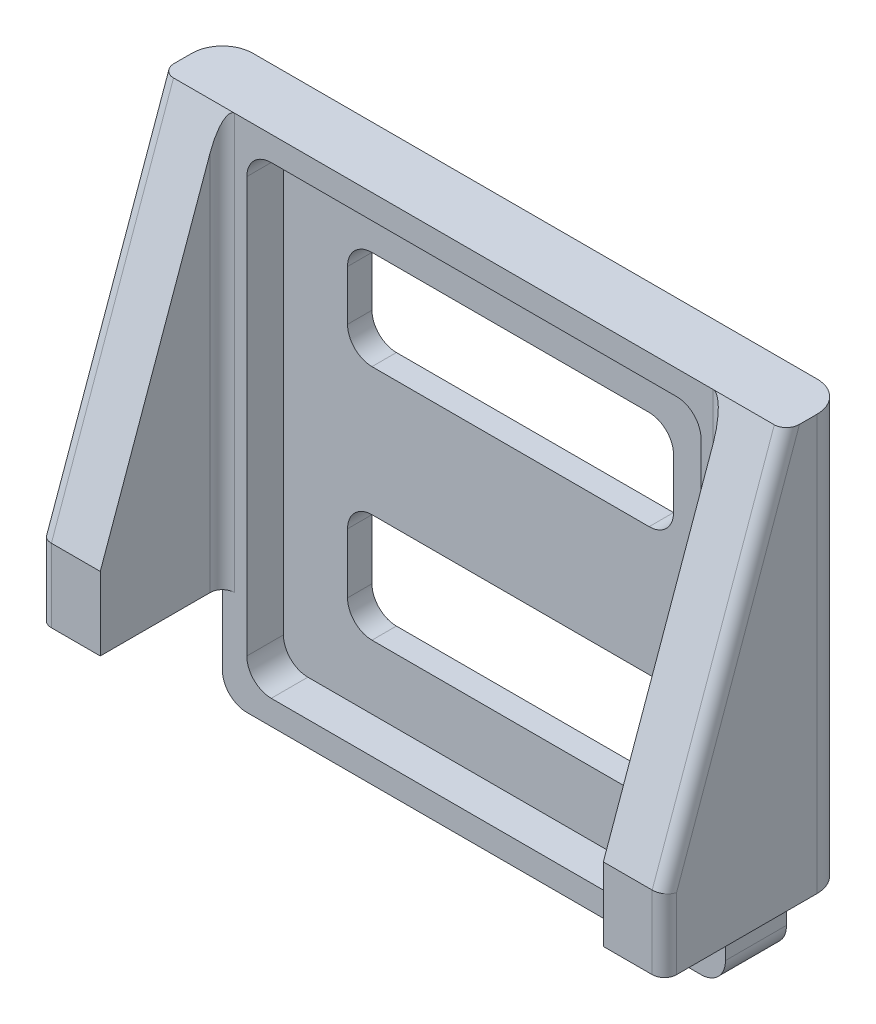
SolidWorks part; units mm, degrees
ref_plane "Front Plane" through (0, 0, 0) normal (0, 0, 1) x (1, 0, 0)
ref_plane "Top Plane" through (0, 0, 0) normal (0, 1, 0) x (1, 0, 0)
ref_plane "Right Plane" through (0, 0, 0) normal (1, 0, 0) x (0, 0, -1)
sketch "Sketch1" plane through (0, 0, 0) normal (0, 0, 1) x (1, 0, 0)
  line L1 (0, 0) -> (41.2, 0)
  line L2 (0, 0) -> (0, -42)
  line L3 (0, -42) -> (41.2, -42)
  line L4 (41.2, 0) -> (41.2, -42)
  dimension "D1" = 41.2
  dimension "D2" = 42
extrude "Boss-Extrude1" add sketch "Sketch1" along normal blind 5 contours L1 L4 L3 L2
sketch "Sketch2" plane through (0, 0, 5) normal (0, 0, 1) x (1, 0, 0)
  line L0 (0, 0) -> (41.2, 0) construction
  line L1 (4, -2) -> (37.2, -2)
  line L2 (2, -4) -> (2, -38)
  line L3 (4, -40) -> (37.2, -40)
  line L4 (39.2, -4) -> (39.2, -38)
  line L5 (0, -42) -> (41.2, -42) construction
  line L6 (0, 0) -> (0, -42) construction
  line L7 (41.2, 0) -> (41.2, -42) construction
  arc A0 (37.2, -2) -> (39.2, -4) centre (37.2, -4) cw
  arc A1 (37.2, -40) -> (39.2, -38) centre (37.2, -38) ccw
  arc A2 (2, -38) -> (4, -40) centre (4, -38) ccw
  arc A3 (4, -2) -> (2, -4) centre (4, -4) ccw
  dimension "D5" = 2
  dimension "D1" = 2
  dimension "D2" = 2
  dimension "D3" = 2
  dimension "D4" = 2
extrude "Cut-Extrude1" cut sketch "Sketch2" against normal blind 3
sketch "Sketch3" plane through (0, 0, 2) normal (0, 0, 1) x (1, 0, 0)
  line L0 (37.2, -2) -> (4, -2) construction
  line L1 (9.25, -7.25) -> (31.95, -7.25)
  line L2 (7.25, -9.25) -> (7.25, -13.35)
  line L3 (9.25, -15.35) -> (31.95, -15.35)
  line L4 (33.95, -9.25) -> (33.95, -13.35)
  line L5 (9.25, -25.85) -> (31.95, -25.85)
  line L6 (7.25, -27.85) -> (7.25, -32.75)
  line L7 (9.25, -34.75) -> (31.95, -34.75)
  line L8 (33.95, -27.85) -> (33.95, -32.75)
  line L9 (4, -40) -> (37.2, -40) construction
  line L10 (2, -4) -> (2, -38) construction
  line L11 (39.2, -38) -> (39.2, -4) construction
  arc A0 (31.95, -34.75) -> (33.95, -32.75) centre (31.95, -32.75) ccw
  arc A1 (7.25, -32.75) -> (9.25, -34.75) centre (9.25, -32.75) ccw
  arc A2 (9.25, -25.85) -> (7.25, -27.85) centre (9.25, -27.85) ccw
  arc A3 (31.95, -25.85) -> (33.95, -27.85) centre (31.95, -27.85) cw
  arc A4 (31.95, -7.25) -> (33.95, -9.25) centre (31.95, -9.25) cw
  arc A5 (31.95, -15.35) -> (33.95, -13.35) centre (31.95, -13.35) ccw
  arc A6 (7.25, -13.35) -> (9.25, -15.35) centre (9.25, -13.35) ccw
  arc A7 (9.25, -7.25) -> (7.25, -9.25) centre (9.25, -9.25) ccw
  dimension "D9" = 2
  dimension "D1" = 5.25
  dimension "D2" = 5.25
  dimension "D3" = 5.25
  dimension "D4" = 5.25
  dimension "D5" = 5.25
  dimension "D6" = 5.25
  dimension "D7" = 10.5
  dimension "D8" = 8.1
extrude "Cut-Extrude2" cut sketch "Sketch3" against normal up to surface (2 mm away) up to face at (20.6, -21, 0)
ref_plane "Plane1" through (0, -34, 0) normal (0, -1, 0) x (-1, 0, 0)
sketch "Sketch6" plane through (41.2, 0, 0) normal (1, 0, 0) x (0, 0, -1)
  line L0 (-5, 0) -> (-5, -42) construction
  line L1 (-5, -28) -> (0, -28)
  line L2 (-5, -28) -> (-5, -34)
  line L3 (-5, -34) -> (0, -34)
  line L4 (0, -28) -> (0, -34)
  line L5 (0, 0) -> (0, -42) construction
  line L6 (-12.2851, -34) -> (12.2851, -34) construction
  dimension "D1" = 6
sketch "Sketch7" plane through (0, 0, 0) normal (-1, 0, 0) x (0, 0, 1)
  line L0 (0, 0) -> (0, -42) construction
  line L1 (0, -28) -> (5, -28)
  line L2 (0, -28) -> (0, -34)
  line L3 (0, -34) -> (5, -34)
  line L4 (5, -28) -> (5, -34)
  line L5 (5, 0) -> (5, -42) construction
  line L6 (-12.2851, -34) -> (12.2851, -34) construction
  dimension "D1" = 6
sketch "Sketch8" plane through (0, 0, 0) normal (0, 0, -1) x (-1, 0, 0)
  line L0 (-33.95, -27.85) -> (-33.95, -32.75) construction
  line L1 (-41.2, -28) -> (-33.95, -28)
  line L2 (-41.2, -28) -> (-41.2, -34)
  line L3 (-41.2, -34) -> (-33.95, -34)
  line L4 (-33.95, -28) -> (-33.95, -34)
  line L5 (-12.2851, -34) -> (12.2851, -34) construction
sketch "Sketch9" plane through (0, 0, 0) normal (0, 0, -1) x (-1, 0, 0)
  line L0 (-7.25, -32.75) -> (-7.25, -27.85) construction
  line L1 (0, -28) -> (-7.25, -28)
  line L2 (0, -28) -> (0, -34)
  line L3 (0, -34) -> (-7.25, -34)
  line L4 (-7.25, -28) -> (-7.25, -34)
  line L5 (-12.2851, -34) -> (12.2851, -34) construction
extrude "Boss-Extrude2" add sketch "Sketch6" along normal blind 5
extrude "Boss-Extrude3" add sketch "Sketch7" along normal blind 5
extrude "Boss-Extrude4" [suppressed] add sketch "Sketch8" along normal blind 6
extrude "Boss-Extrude5" [suppressed] add sketch "Sketch9" along normal blind 6
sketch "Sketch13" plane through (0, 0, 5) normal (0, 0, 1) x (1, 0, 0)
  line L1 (46.2, -34) -> (41.2, -34)
  line L2 (46.2, -34) -> (46.2, -28)
  line L3 (46.2, -28) -> (41.2, -28)
  line L4 (41.2, -34) -> (41.2, -28)
  line L5 (0, -34) -> (-5, -34)
  line L6 (0, -34) -> (0, -28)
  line L7 (0, -28) -> (-5, -28)
  line L8 (-5, -34) -> (-5, -28)
extrude "Boss-Extrude6" add sketch "Sketch13" along normal blind 10
ref_plane "Plane2" through (20.6, 0, 0) normal (1, 0, 0) x (0, 0, -1)
sketch "Sketch10" plane through (0, -28, 0) normal (0, 1, 0) x (1, 0, 0)
  line L0 (41.2, -7.5) -> (46.2, -7.5) construction
  line L3 (43.7, -15) -> (43.7, 0) construction
  line L5 (46.2, 0) -> (41.2, 0) construction
  line L6 (46.2, -15) -> (41.2, -15) construction
  line L7 (46.2, 0) -> (46.2, -15) construction
  line L8 (41.2, 0) -> (41.2, -5) construction
  circle A0 centre (43.7, -3) radius 1.5
  circle A1 centre (43.7, -12) radius 1.5
  point P2 (0, 0)
  point P16 (46.2, -7.5)
  dimension "D1" = 3
  dimension "D2" = 4.5
extrude "Cut-Extrude3" cut sketch "Sketch10" against normal blind 6
mirror "Mirror1" about plane through (20.6, 0, 0) normal (1, 0, 0) of "Cut-Extrude3"
sketch "Sketch12" [suppressed] plane through (0, -28, 0) normal (0, 1, 0) x (1, 0, 0)
  line L0 (37.575, 0) -> (37.575, 6) construction
  line L1 (33.95, 0) -> (41.2, 0) construction
  line L2 (33.95, 6) -> (41.2, 6) construction
  line L3 (41.2, 3) -> (33.95, 3) construction
  line L4 (41.2, 6) -> (41.2, 0) construction
  line L5 (33.95, 6) -> (33.95, 0) construction
  circle A0 centre (37.575, 3) radius 1.5
  dimension "D1" = 3
extrude "Cut-Extrude4" [suppressed] cut sketch "Sketch12" against normal blind 6
mirror "Mirror2" [suppressed] about plane through (20.6, 0, 0) normal (1, 0, 0)
fillet "Fillet3" [suppressed] radius 2
fillet "Fillet4" radius 2.5 2 edges at (46.2, -31, 0) (-5, -31, 0)
sketch "Sketch14" [suppressed] plane through (0, -28, 0) normal (0, 1, 0) x (1, 0, 0)
  line L0 (41.2, 3.5) -> (38.7, 6)
  line L3 (41.2, 6) -> (41.2, 0) construction
  line L6 (35.95, 6) -> (41.2, 6) construction
  dimension "D1" = 2.5
  dimension "D2" = 2.5
extrude "Cut-Extrude6" [suppressed] cut sketch "Sketch14" against normal blind 6 and the other way through all flip side to cut
sketch "Sketch15" [suppressed] plane through (0, -28, 0) normal (0, 1, 0) x (1, 0, 0)
  line L0 (2.5, 6) -> (0, 3.5)
  line L3 (0, 6) -> (0, 0) construction
  line L4 (0, 6) -> (7.25, 6) construction
  dimension "D1" = 2.5
  dimension "D2" = 2.5
extrude "Cut-Extrude7" [suppressed] cut sketch "Sketch15" against normal blind 6 and the other way through all flip side to cut
sketch "Sketch16" plane through (0, -28, 0) normal (0, 1, 0) x (1, 0, 0)
  line L0 (41.2, 0) -> (43.7, 0)
  line L1 (41.2, -5) -> (46.2, -5)
  line L2 (46.2, -2.5) -> (46.2, -15) construction
  line L3 (46.2, -5) -> (46.2, -2.5)
  line L5 (41.2, 0) -> (41.2, -5)
  arc A0 (46.2, -2.5) -> (43.7, 0) centre (43.7, -2.5) ccw
extrude "Boss-Extrude7" add sketch "Sketch16" along normal up to surface (28 mm away) up to face at (20.6, 0, 2.5)
ref_plane "Plane3" through (43.7, 0, 0) normal (1, 0, 0) x (0, 0, -1)
ref_plane "Plane4" through (20.6, 0, 0) normal (1, 0, 0) x (0, 0, -1)
sketch "Sketch17" plane through (46.2, 0, 0) normal (1, 0, 0) x (0, 0, -1)
  line L0 (-5, 0) -> (-15, -28)
  line L1 (-15, -28) -> (-5, -28)
  line L2 (-5, 0) -> (-5, -28) construction
  line L3 (-5, -28) -> (-15, -28) construction
  line L4 (-5, -28) -> (-5, 0)
extrude "Boss-Extrude8" add sketch "Sketch17" against normal blind 5
fillet "Fillet10" radius 1 2 edges at (46.2, -31, 15) (46.2, -14, 10)
mirror "Mirror3" about plane through (20.6, 0, 0) normal (1, 0, 0) of "Boss-Extrude7", "Boss-Extrude8"
fillet "Fillet12" radius 2 2 edges at (41.2, -42, 2.5) (0, -42, 2.5)
fillet "Fillet13" radius 1 2 edges at (-5, -31, 15) (-5, -14, 10)
fillet "Fillet14" radius 1 2 edges at (41.2, -17, 5) (0, -17, 5)
